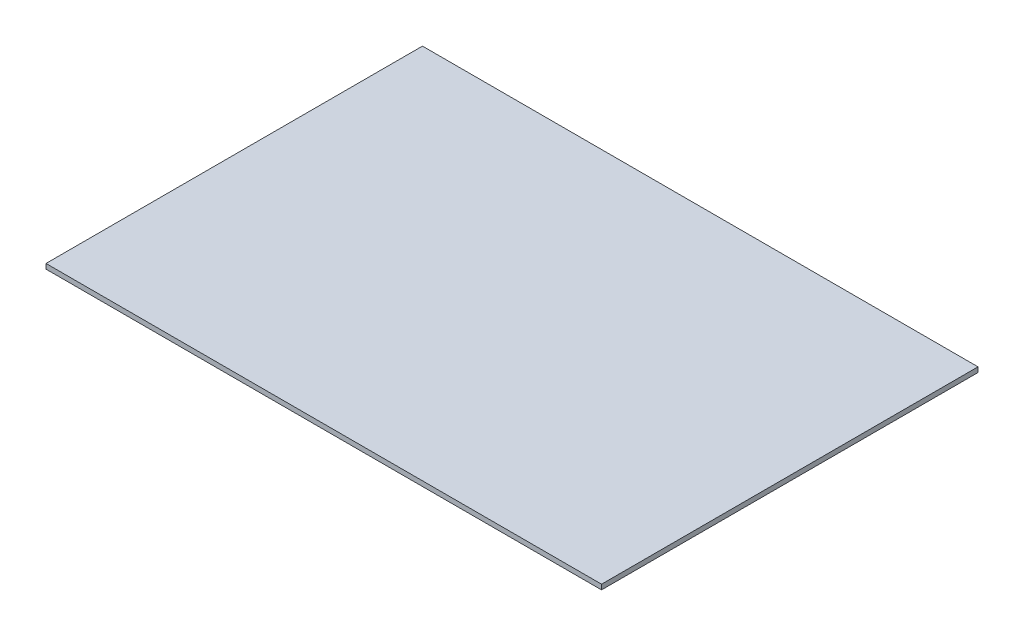
SolidWorks part; units mm, degrees
ref_plane "Front Plane" through (0, 0, 0) normal (0, 0, 1) x (1, 0, 0)
ref_plane "Top Plane" through (0, 0, 0) normal (0, 1, 0) x (1, 0, 0)
ref_plane "Right Plane" through (0, 0, 0) normal (1, 0, 0) x (0, 0, -1)
sketch "Sketch1" plane through (0, 0, 0) normal (0, 1, 0) x (1, 0, 0)
  line L1 (0, 0) -> (336, 0)
  line L2 (0, 0) -> (0, 227.69)
  line L3 (0, 227.69) -> (336, 227.69)
  line L4 (336, 0) -> (336, 227.69)
  line L5 (0, 0) -> (336, 227.69) construction
  line L6 (0, 227.69) -> (336, 0) construction
  point P4 (168, 113.845)
  dimension "D1" = 336
  dimension "D2" = 227.69
extrude "Boss-Extrude1" add sketch "Sketch1" along normal blind 3
